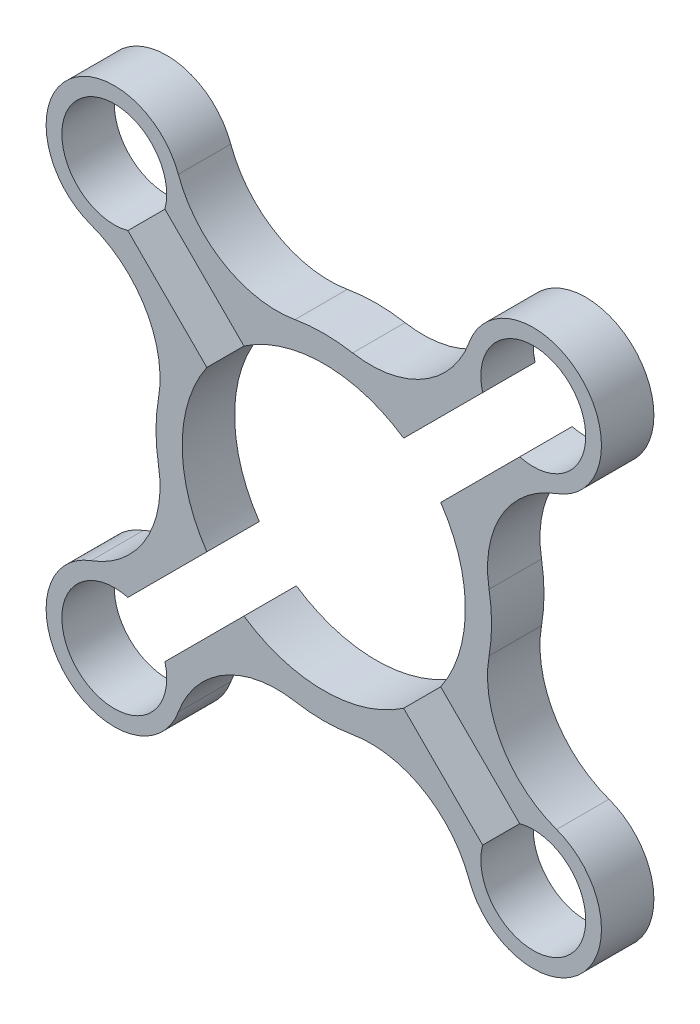
SolidWorks part; units mm, degrees
ref_plane "Front Plane" through (0, 0, 0) normal (0, 0, 1) x (1, 0, 0)
ref_plane "Top Plane" through (0, 0, 0) normal (0, 1, 0) x (1, 0, 0)
ref_plane "Right Plane" through (0, 0, 0) normal (1, 0, 0) x (0, 0, -1)
sketch "Sketch1" plane through (0, 0, 0) normal (0, 0, 1) x (1, 0, 0)
  line L0 (0, 0) -> (39.9515, 39.9515) construction
  line L1 (0, 0) -> (87.3579, 0) construction
  line L2 (3.5355, -3.5355) -> (7.0711, 0)
  line L3 (15.2261, 22.2972) -> (30.2923, 37.3633)
  line L4 (36.2593, 43.3303) -> (36.416, 43.4871)
  line L5 (43.3303, 36.2593) -> (43.4871, 36.416)
  line L6 (-3.5355, 3.5355) -> (36.416, 43.4871) construction
  line L7 (22.2972, 15.2261) -> (37.3633, 30.2923)
  line L8 (3.5355, -3.5355) -> (43.4871, 36.416) construction
  line L9 (15.2261, -22.2972) -> (30.2923, -37.3633)
  line L10 (22.2972, -15.2261) -> (37.3633, -30.2923)
  line L11 (-22.2972, -15.2261) -> (-37.3633, -30.2923)
  line L12 (-15.2261, -22.2972) -> (-30.2923, -37.3633)
  line L13 (-15.2261, 22.2972) -> (-30.2923, 37.3633)
  line L14 (-22.2972, 15.2261) -> (-37.3633, 30.2923)
  arc A0 (15.2261, 22.2972) -> (-15.2261, 22.2972) centre (0, 0) ccw
  arc A1 (5.4999, 31.5238) -> (-5.4999, 31.5238) centre (0, 0) ccw
  circle A2 centre (0, 0) radius 56.5 construction
  arc A3 (37.3633, 30.2923) -> (30.2923, 37.3633) centre (39.9515, 39.9515) ccw
  arc A4 (44.3931, 27.7338) -> (27.7338, 44.3931) centre (39.9515, 39.9515) ccw
  arc A5 (5.4999, 31.5238) -> (27.7338, 44.3931) centre (8.9373, 51.2262) ccw
  arc A6 (31.5238, 5.4999) -> (44.3931, 27.7338) centre (51.2262, 8.9373) cw
  arc A7 (31.5238, -5.4999) -> (44.3931, -27.7338) centre (51.2262, -8.9373) ccw
  arc A8 (27.7338, -44.3931) -> (44.3931, -27.7338) centre (39.9515, -39.9515) ccw
  arc A9 (30.2923, -37.3633) -> (37.3633, -30.2923) centre (39.9515, -39.9515) ccw
  arc A10 (5.4999, -31.5238) -> (27.7338, -44.3931) centre (8.9373, -51.2262) cw
  arc A11 (-5.4999, -31.5238) -> (-27.7338, -44.3931) centre (-8.9373, -51.2262) ccw
  arc A12 (-44.3931, -27.7338) -> (-27.7338, -44.3931) centre (-39.9515, -39.9515) ccw
  arc A13 (-37.3633, -30.2923) -> (-30.2923, -37.3633) centre (-39.9515, -39.9515) ccw
  arc A14 (-31.5238, -5.4999) -> (-44.3931, -27.7338) centre (-51.2262, -8.9373) cw
  arc A15 (-31.5238, 5.4999) -> (-44.3931, 27.7338) centre (-51.2262, 8.9373) ccw
  arc A16 (-27.7338, 44.3931) -> (-44.3931, 27.7338) centre (-39.9515, 39.9515) ccw
  arc A17 (-30.2923, 37.3633) -> (-37.3633, 30.2923) centre (-39.9515, 39.9515) ccw
  arc A18 (-5.4999, 31.5238) -> (-27.7338, 44.3931) centre (-8.9373, 51.2262) cw
  arc A19 (-22.2972, 15.2261) -> (-22.2972, -15.2261) centre (0, 0) ccw
  arc A20 (-31.5238, 5.4999) -> (-31.5238, -5.4999) centre (0, 0) ccw
  arc A21 (-5.4999, -31.5238) -> (5.4999, -31.5238) centre (0, 0) ccw
  arc A22 (-15.2261, -22.2972) -> (15.2261, -22.2972) centre (0, 0) ccw
  arc A23 (22.2972, -15.2261) -> (22.2972, 15.2261) centre (0, 0) ccw
  arc A24 (31.5238, -5.4999) -> (31.5238, 5.4999) centre (0, 0) ccw
  point P58 (0, 0)
  dimension "D1" = 54
  dimension "D2" = 64
  dimension "D3" = 113
  dimension "D4" = 20
  dimension "D5" = 26
  dimension "D9" = 20
  dimension "D6" = 45
  dimension "D7" = 5
  dimension "D8" = 5
  dimension "D10" = 4
extrude "Boss-Extrude1" add sketch "Sketch1" along normal mid plane 10 contours A7 A24 A6 A4 A5 A1 A18 A16 A15 A20 A14 A12 A11 A21 A10 A8 A23 L10 A9 L9 A22 L12 A13 L11 A19 L14 A17 L13 A0 L3 A3 L7
